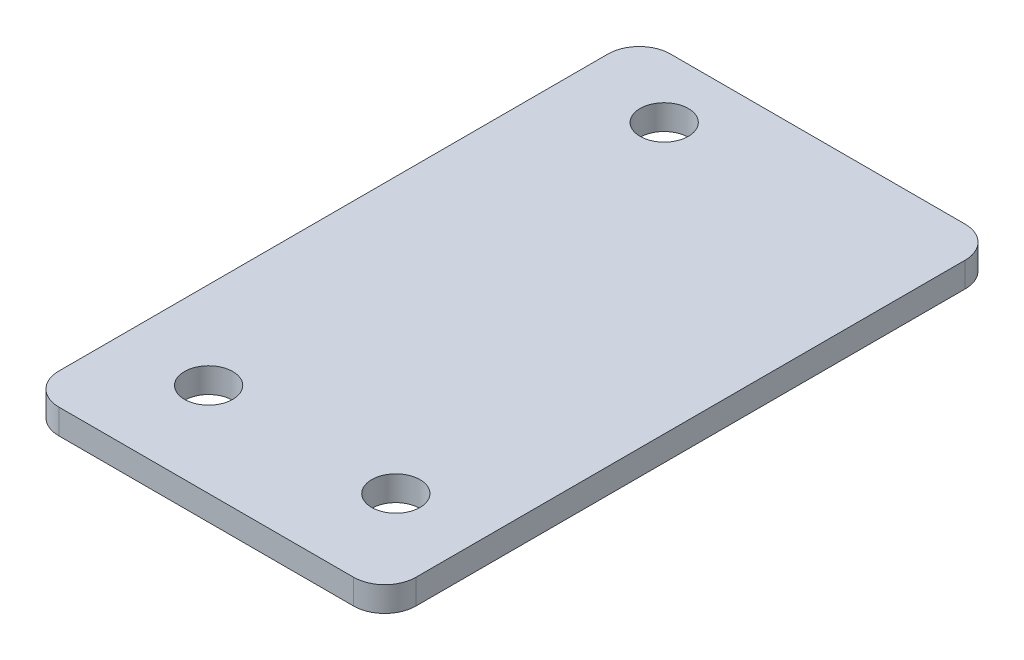
SolidWorks part; units mm, degrees
material "AISI 4340 Steel, normalized"
ref_plane "X-Y Datum" through (0, 0, 0) normal (0, 0, 1) x (1, 0, 0)
ref_plane "X-Z Datum" through (0, 0, 0) normal (0, 1, 0) x (1, 0, 0)
ref_plane "Y-Z Datum" through (0, 0, 0) normal (1, 0, 0) x (0, 0, -1)
sketch "Sketch1" plane through (0, 0, 0) normal (0, 1, 0) x (1, 0, 0)
  line L0 (0, 57.3773) -> (36.1544, 57.3773) construction
  line L1 (3.175, -4.8527) -> (33.1644, -4.8527)
  line L2 (0, -1.6777) -> (0, 54.2023)
  line L3 (3.175, 57.3773) -> (33.1644, 57.3773)
  line L4 (36.3394, -1.6777) -> (36.3394, 54.2023)
  arc A0 (36.3394, -1.6777) -> (33.1644, -4.8527) centre (33.1644, -1.6777) cw
  arc A1 (36.3394, 54.2023) -> (33.1644, 57.3773) centre (33.1644, 54.2023) ccw
  arc A2 (0, 54.2023) -> (3.175, 57.3773) centre (3.175, 54.2023) cw
  arc A3 (0, -1.6777) -> (3.175, -4.8527) centre (3.175, -1.6777) ccw
  circle A4 centre (8.89, 51.0273) radius 2.4574 construction
  circle A5 centre (27.94, 4.6723) radius 2.4574 construction
  circle A6 centre (8.89, 4.6723) radius 2.4574 construction
  circle A7 centre (8.89, 51.0273) radius 2.4574
  circle A8 centre (27.94, 4.6723) radius 2.4574
  circle A9 centre (8.89, 4.6723) radius 2.4574
  point P10 (36.3394, -4.8527)
  point P13 (36.3394, 57.3773)
  point P16 (0, 57.3773)
  dimension "D3" = 3.175
  dimension "D1" = 62.23
  dimension "D2" = 36.3394
extrude "Boss-Extrude1" add sketch "Sketch1" against normal blind 2.54
